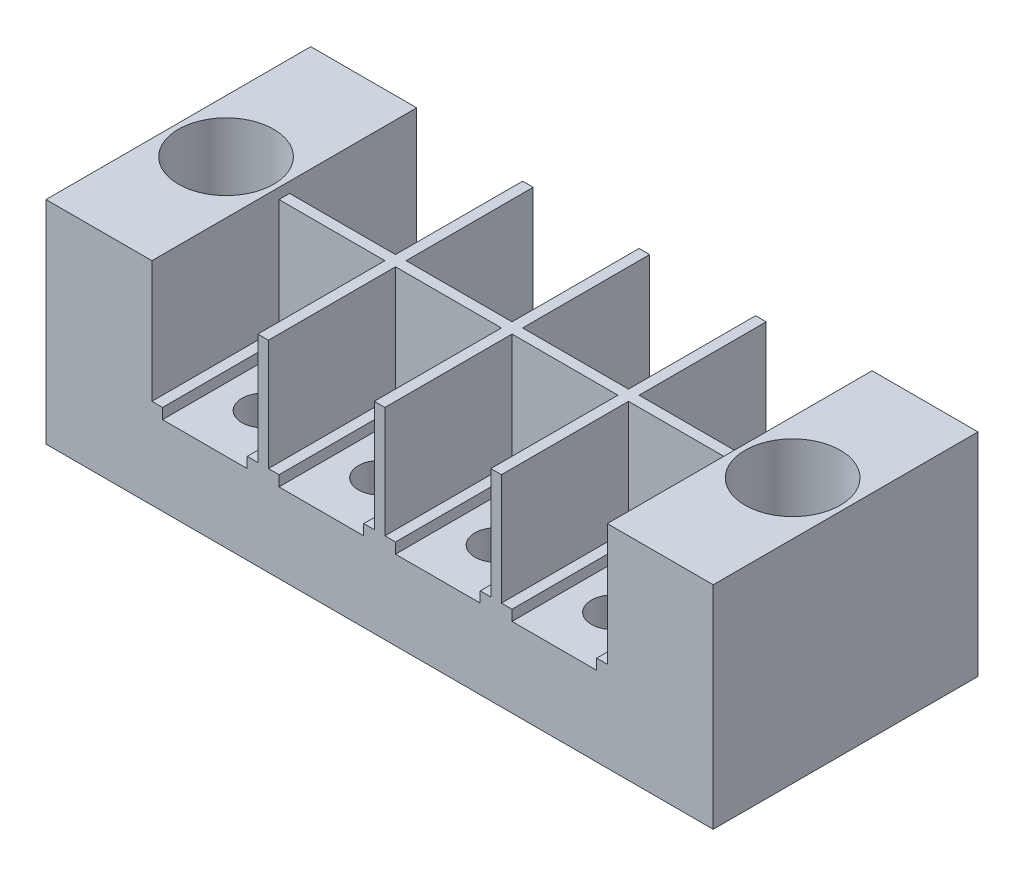
SolidWorks part; units mm, degrees
ref_plane "Front Plane" through (0, 0, 0) normal (0, 0, 1) x (1, 0, 0)
ref_plane "Top Plane" through (0, 0, 0) normal (0, 1, 0) x (1, 0, 0)
ref_plane "Right Plane" through (0, 0, 0) normal (1, 0, 0) x (0, 0, -1)
sketch "Sketch2" plane through (0, 0, 0) normal (0, 1, 0) x (1, 0, 0)
  line L0 (0, 62.8678) -> (0, -62.8678) construction
  line L1 (83.0329, 0) -> (-83.0329, 0) construction
  line L3 (31.5, 12.5) -> (-31.5, 12.5)
  line L4 (31.5, 12.5) -> (31.5, -12.5)
  line L5 (31.5, -12.5) -> (-31.5, -12.5)
  line L6 (-31.5, 12.5) -> (-31.5, -12.5)
  line L7 (31.5, 12.5) -> (-31.5, -12.5) construction
  line L8 (31.5, -12.5) -> (-31.5, 12.5) construction
  point P0 (0, 0)
  point P4 (0, 0)
  point P8 (0, 0)
extrude "Boss-Extrude2" add sketch "Sketch2" along normal blind 20
sketch "Sketch5" plane through (0, 20, 0) normal (0, 1, 0) x (1, 0, 0)
  line L0 (-31.5, -12.5) -> (31.5, -12.5) construction
  line L1 (-31.5, 12.5) -> (-21.5, 12.5)
  line L2 (-31.5, 12.5) -> (-31.5, -12.5)
  line L3 (-31.5, -12.5) -> (-21.5, -12.5)
  line L4 (-21.5, 12.5) -> (-21.5, -12.5)
  line L6 (-21.5, 12.5) -> (21.5, 12.5)
  line L7 (-21.5, 12.5) -> (-21.5, -12.5)
  line L8 (-21.5, -12.5) -> (21.5, -12.5)
  line L9 (21.5, 12.5) -> (21.5, -12.5)
  line M2 (-31.5, -12.5) -> (31.5, -12.5)
  line M4 (31.5, 12.5) -> (-31.5, 12.5)
extrude "Cut-Extrude2" cut sketch "Sketch5" against normal blind 1 contours L9 L4 M4 M2
sketch "Sketch6" plane through (0, 19, 0) normal (0, 1, 0) x (1, 0, 0)
  line L0 (21.5, 0.5) -> (21.5, -0.5)
  line L1 (21.5, 12.5) -> (21.5, -12.5) construction
  line L2 (21.5, -0.5) -> (-21.5, -0.5)
  line L3 (-21.5, 12.5) -> (-21.5, -12.5) construction
  line L4 (-21.5, -0.5) -> (-21.5, 0.5)
  line L5 (-21.5, 0.5) -> (21.5, 0.5)
  line L6 (-21.5, 0.5) -> (-11.5, 0.5)
  line L7 (-21.5, 12.5) -> (21.5, 12.5)
  line L8 (-21.5, 12.5) -> (-21.5, -12.5)
  line L9 (-21.5, -12.5) -> (21.5, -12.5)
  line L10 (21.5, 12.5) -> (21.5, -12.5)
  line L11 (-11.5, 0.5) -> (-11.5, 12.5)
  line L12 (-11.5, 12.5) -> (-10.5, 12.5)
  line L13 (-10.5, 12.5) -> (-10.5, 0.5)
  line L14 (-10.5, 0.5) -> (-0.5, 0.5)
  line L15 (-0.5, 0.5) -> (-0.5, 12.5)
  line L16 (-0.5, 12.5) -> (0.5, 12.5)
  line L17 (0.5, 12.5) -> (0.5, 0.5)
  line L18 (0.5, 0.5) -> (10.5, 0.5)
  line L19 (10.5, 0.5) -> (10.5, 12.5)
  line L20 (10.5, 12.5) -> (11.5, 12.5)
  line L21 (11.5, 12.5) -> (11.5, 0.5)
  line L22 (-21.5, 0) -> (21.5, 0) construction
  line L23 (11.5, -12.5) -> (11.5, -0.5)
  line L24 (10.5, -0.5) -> (10.5, -12.5)
  line L25 (0.5, -12.5) -> (0.5, -0.5)
  line L26 (-0.5, -0.5) -> (-0.5, -12.5)
  line L27 (-10.5, -12.5) -> (-10.5, -0.5)
  line L28 (-11.5, -0.5) -> (-11.5, -12.5)
  point P5 (21.5, 0)
  line M16 (21.5, -12.5) -> (21.5, 12.5)
  line M17 (21.5, 12.5) -> (-21.5, 12.5)
  line M18 (-21.5, 12.5) -> (-21.5, -12.5)
  line M19 (-21.5, -12.5) -> (21.5, -12.5)
extrude "Cut-Extrude3" cut sketch "Sketch6" against normal blind 10 contours L5 L11 L7 M18 | L28 L2 M18 M19 | L27 L9 L26 L2 | L5 L15 L7 L13 | L5 L19 L7 L17 | L25 L9 L24 L2 | L23 L9 L2 M16 | L21 L5 M17 M16
sketch "Sketch7" plane through (0, 0, 12.5) normal (0, 0, 1) x (1, 0, 0)
  line L0 (-21.5, 9) -> (-11.5, 9)
  line L1 (-11.5, 9) -> (-11.5, 8.5)
  line L2 (-11.5, 8.5) -> (-12.5, 8.5)
  line L3 (-12.5, 8.5) -> (-12.5, 7.5)
  line L4 (-12.5, 7.5) -> (-20.5, 7.5)
  line L5 (-20.5, 7.5) -> (-20.5, 8.5)
  line L6 (-20.5, 8.5) -> (-21.5, 8.5)
  line L7 (-21.5, 8.5) -> (-21.5, 9)
  line L8 (-10.5, 9) -> (-0.5, 9)
  line L9 (-0.5, 9) -> (-0.5, 8.5)
  line L10 (-0.5, 8.5) -> (-1.5, 8.5)
  line L11 (-1.5, 8.5) -> (-1.5, 7.5)
  line L12 (-1.5, 7.5) -> (-9.5, 7.5)
  line L13 (-9.5, 7.5) -> (-9.5, 8.5)
  line L14 (-9.5, 8.5) -> (-10.5, 8.5)
  line L15 (-10.5, 8.5) -> (-10.5, 9)
  line L16 (0.5, 9) -> (10.5, 9)
  line L17 (10.5, 9) -> (10.5, 8.5)
  line L18 (10.5, 8.5) -> (9.5, 8.5)
  line L19 (9.5, 8.5) -> (9.5, 7.5)
  line L20 (9.5, 7.5) -> (1.5, 7.5)
  line L21 (1.5, 7.5) -> (1.5, 8.5)
  line L22 (1.5, 8.5) -> (0.5, 8.5)
  line L23 (0.5, 8.5) -> (0.5, 9)
  line L24 (11.5, 9) -> (21.5, 9)
  line L25 (21.5, 9) -> (21.5, 8.5)
  line L26 (21.5, 8.5) -> (20.5, 8.5)
  line L27 (20.5, 8.5) -> (20.5, 7.5)
  line L28 (20.5, 7.5) -> (12.5, 7.5)
  line L29 (12.5, 7.5) -> (12.5, 8.5)
  line L30 (12.5, 8.5) -> (11.5, 8.5)
  line L31 (11.5, 8.5) -> (11.5, 9)
extrude "Cut-Extrude4" cut sketch "Sketch7" against normal blind 24
sketch "Sketch8" plane through (0, 0, 0) normal (0, -1, 0) x (1, 0, 0)
  line L0 (31.5, -12.5) -> (-31.5, -12.5) construction
  line L1 (-31.5, 12.5) -> (-21.5, 12.5)
  line L2 (-31.5, 12.5) -> (-31.5, -12.5)
  line L3 (-31.5, -12.5) -> (-21.5, -12.5)
  line L4 (-21.5, 12.5) -> (-21.5, -12.5)
  line L5 (-21.5, -1.5) -> (-21.5, 1.5)
  line L6 (31.5, 12.5) -> (21.5, 12.5)
  line L7 (31.5, 12.5) -> (31.5, -12.5)
  line L8 (31.5, -12.5) -> (21.5, -12.5)
  line L9 (21.5, 12.5) -> (21.5, -12.5)
  line L10 (-21.5, 1.5) -> (21.5, 1.5)
  line L11 (21.5, 1.5) -> (21.5, -1.5)
  line L12 (21.5, -1.5) -> (-21.5, -1.5)
  point P15 (-21.5, 0)
extrude "Cut-Extrude5" cut sketch "Sketch8" against normal blind 8 contours L12 L9 L10 L4
sketch "Sketch9" plane through (0, 7.5, 0) normal (0, 1, 0) x (1, 0, 0)
  line L0 (-21.5, 0) -> (21.5, 0) construction
  line L1 (-21.5, 0.5) -> (-21.5, -0.5) construction
  line L2 (21.5, 0.5) -> (21.5, -0.5) construction
  circle A0 centre (-16.5, -7) radius 2
  circle A1 centre (-5.5, -7) radius 2
  circle A2 centre (5.5, -7) radius 2
  circle A3 centre (16.5, -7) radius 2
  circle A4 centre (16.5, 7) radius 2
  circle A5 centre (5.5, 7) radius 2
  circle A6 centre (-5.5, 7) radius 2
  circle A7 centre (-16.5, 7) radius 2
extrude "Cut-Extrude6" cut sketch "Sketch9" against normal blind 4
sketch "Sketch10" plane through (0, 20, 0) normal (0, 1, 0) x (1, 0, 0)
  circle A0 centre (26.5, 0) radius 4.5
  circle A1 centre (-26.5, -0.5) radius 4.5
extrude "Cut-Extrude7" cut sketch "Sketch10" against normal blind 19
sketch "Sketch11" plane through (0, 1, 0) normal (0, 1, 0) x (1, 0, 0)
  circle A0 centre (-26.5, -0.5) radius 2
  circle A1 centre (26.5, 0) radius 2
extrude "Cut-Extrude8" cut sketch "Sketch11" against normal blind 19
